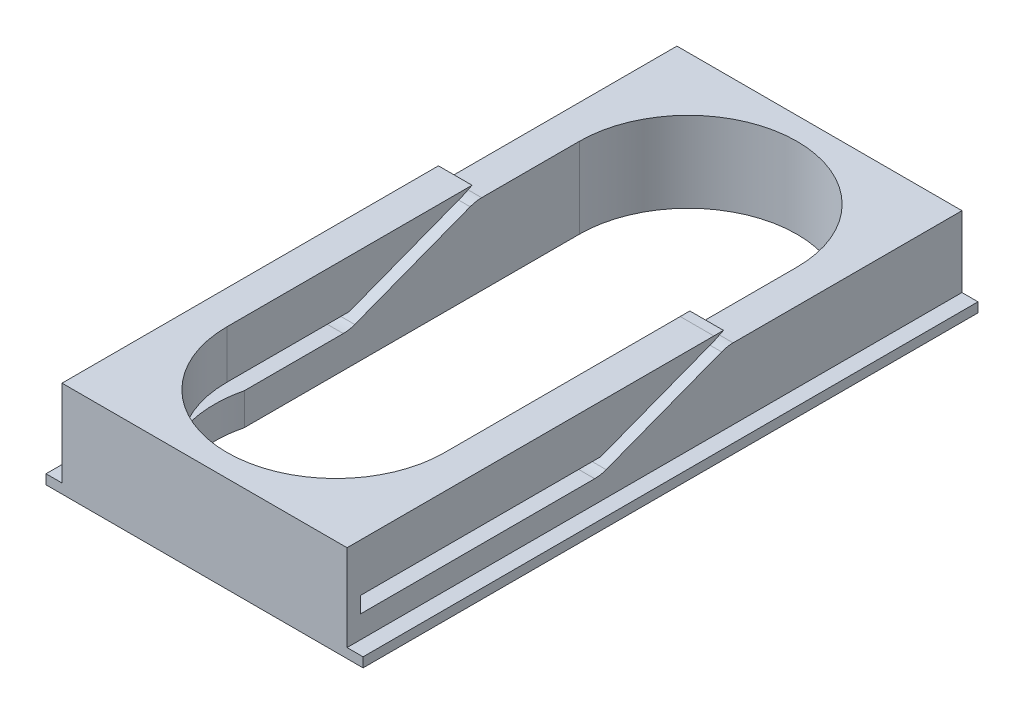
SolidWorks part; units mm, degrees
ref_plane "Front Plane" through (0, 0, 0) normal (0, 0, 1) x (1, 0, 0)
ref_plane "Top Plane" through (0, 0, 0) normal (0, 1, 0) x (1, 0, 0)
ref_plane "Right Plane" through (0, 0, 0) normal (1, 0, 0) x (0, 0, -1)
sketch "Sketch1" plane through (0, 0, 0) normal (0, 1, 0) x (1, 0, 0)
  line L0 (-10.5, -34.9563) -> (-10.5, 75.0437) construction
  line L1 (-55, -75.9563) -> (34, -75.9563)
  line L2 (-55, -75.9563) -> (-55, 116.0437)
  line L3 (-55, 116.0437) -> (34, 116.0437)
  line L4 (34, -75.9563) -> (34, 116.0437)
  line L5 (-44.5, -34.9563) -> (-44.5, 75.0437)
  line L6 (23.5, -34.9563) -> (23.5, 75.0437)
  arc A0 (-44.5, -34.9563) -> (23.5, -34.9563) centre (-10.5, -34.9563) ccw
  arc A1 (23.5, 75.0437) -> (-44.5, 75.0437) centre (-10.5, 75.0437) ccw
  point P6 (-10.5, 20.0437)
  dimension "D3" = 10.5
  dimension "D4" = 41
  dimension "D1" = 34
  dimension "D2" = 41
  dimension "D6" = 10.5
extrude "Boss-Extrude1" add sketch "Sketch1" along normal blind 30
sketch "Sketch2" plane through (0, 0, 0) normal (0, -1, 0) x (1, 0, 0)
  circle A0 centre (-10.5, 37.8388) radius 34.9994
extrude "Cut-Extrude1" cut sketch "Sketch2" against normal blind 10
sketch "Sketch3" plane through (34, 0, 0) normal (1, 0, 0) x (0, 0, -1)
  line L0 (-75.9563, 0) -> (116.0437, 0) construction
  line L1 (-71.7863, 10) -> (3.2137, 10)
  line L2 (-71.7863, 10) -> (-71.7863, 15)
  line L3 (-71.7863, 15) -> (3.2137, 15)
  line L4 (3.2137, 10) -> (3.2137, 15)
  dimension "D1" = 5
  dimension "D2" = 10
  dimension "D3" = 75
extrude "Cut-Extrude2" cut sketch "Sketch3" against normal blind 102
sketch "Sketch4" plane through (-55, 0, 0) normal (-1, 0, 0) x (0, 0, 1)
  line L1 (-40.9707, 29.4694) -> (-41.2116, 24.5617)
  line L4 (-40.9707, 29.4694) -> (-3.2137, 15)
  line L5 (-3.2137, 15) -> (-3.2137, 10)
  line L6 (-3.2137, 10) -> (-41.2116, 24.5617)
extrude "Cut-Extrude4" cut sketch "Sketch4" against normal blind 102
sketch "Sketch5" plane through (-55, 0, 0) normal (-1, 0, 0) x (0, 0, 1)
  line L2 (-42.5706, 30) -> (-40.9707, 30)
sketch "Sketch6" plane through (0, 30, 0) normal (0, 1, 0) x (1, 0, 0)
  line L0 (-44.5, 75.0437) -> (-44.5, -34.9563) construction
  line L1 (-55, 42.5706) -> (-44.5, 42.5706)
  line L2 (-55, 42.5706) -> (-55, 38.5706)
  line L3 (-55, 38.5706) -> (-44.5, 38.5706)
  line L4 (-44.5, 42.5706) -> (-44.5, 38.5706)
  line L7 (23.5, 42.5706) -> (23.5, 38.5706)
  line L8 (34, 38.5706) -> (23.5, 38.5706)
  line L9 (34, 42.5706) -> (34, 38.5706)
  line L10 (34, 42.5706) -> (23.5, 42.5706)
  dimension "D1" = 4
extrude "Cut-Extrude7" cut sketch "Sketch6" against normal blind 8
sketch "Sketch7" plane through (-55, 0, 0) normal (-1, 0, 0) x (0, 0, 1)
  line L0 (-38.5706, 23.5496) -> (-42.5706, 25.0825)
  line L1 (-42.5706, 22) -> (-42.5706, 30) construction
  line L2 (-42.5706, 25.0825) -> (-42.5706, 22)
  line L3 (-42.5706, 22) -> (-38.5706, 22)
  line L4 (-38.5706, 22) -> (-38.5706, 23.5496)
extrude "Boss-Extrude2" add sketch "Sketch7" against normal up to surface (10.5 mm away) up to face at (-44.5, 16.3944, -28.5016)
sketch "Sketch8" plane through (-55, 0, 0) normal (-1, 0, 0) x (0, 0, 1)
  line L0 (-42.5706, 25.0825) -> (-55.4025, 30)
  line L1 (-116.0437, 30) -> (-42.5706, 30) construction
  line L2 (-55.4025, 30) -> (-42.5706, 30)
  line L3 (-42.5706, 30) -> (-42.5706, 25.0825)
extrude "Cut-Extrude8" cut sketch "Sketch8" against normal blind 20.7678
sketch "Sketch9" plane through (34, 0, 0) normal (1, 0, 0) x (0, 0, -1)
  line L0 (38.5706, 23.5496) -> (42.5706, 25.0825)
  line L1 (42.5706, 22) -> (42.5706, 30) construction
  line L2 (42.5706, 25.0825) -> (42.5706, 22)
  line L3 (42.5706, 22) -> (38.5706, 22)
  line L4 (38.5706, 22) -> (38.5706, 23.5496)
extrude "Boss-Extrude3" add sketch "Sketch9" against normal up to surface (10.5 mm away) up to face at (23.5, 16.3944, -28.5016)
sketch "Sketch10" plane through (34, 0, 0) normal (1, 0, 0) x (0, 0, -1)
  line L0 (42.5706, 25.0825) -> (55.4025, 30)
  line L1 (42.5706, 30) -> (116.0437, 30) construction
  line L2 (55.4025, 30) -> (42.5706, 30)
  line L3 (42.5706, 30) -> (42.5706, 25.0825)
extrude "Cut-Extrude9" cut sketch "Sketch10" against normal blind 22.8125
sketch "Sketch11" plane through (34, 0, 0) normal (1, 0, 0) x (0, 0, -1)
  line L0 (38.5706, 28.5496) -> (41.5706, 30.0071)
  line L1 (41.5706, 30.0071) -> (38.5706, 30)
  line L4 (38.5706, 30) -> (38.5706, 28.5496)
  point P3 (55.4025, 30)
  dimension "D1" = 3
sketch "Sketch12" plane through (-55, 0, 0) normal (-1, 0, 0) x (0, 0, 1)
  line L0 (-38.5706, 30) -> (-41.5706, 30)
  line L1 (-41.5706, 30) -> (-38.5706, 28.5496)
  line L2 (-38.5706, 28.5496) -> (-38.5706, 30)
  point P3 (-55.4025, 30)
  dimension "D1" = 3
extrude "Boss-Extrude6" add sketch "Sketch12" against normal up to surface (10.5 mm away) up to face at (-44.5, 23.7099, -2.0885)
extrude "Boss-Extrude7" add sketch "Sketch11" against normal up to surface (10.5 mm away) up to face at (23.5, 13.3333, -24.9391)
fillet "Fillet1" radius 10 1 edges at (-49.75, 30, -55.4025)
fillet "Fillet2" radius 10 1 edges at (28.75, 30, -55.4025)
fillet "Fillet3" radius 10 1 edges at (-49.75, 10, -3.2137)
fillet "Fillet4" radius 10 1 edges at (28.75, 10, -3.2137)
sketch "Sketch14" plane through (34, 0, 0) normal (1, 0, 0) x (0, 0, -1)
  line L0 (42.7174, 25.1388) -> (116.0437, 25.1388)
  line L1 (53.6745, 29.3378) -> (4.9417, 10.6622) construction
  line L2 (116.0437, 30) -> (116.0437, 0) construction
  line L3 (42.7174, 25.1388) -> (53.6745, 29.3378)
  line L4 (53.6745, 29.3378) -> (57.253, 30)
  line L5 (57.253, 30) -> (116.0437, 30)
  line L6 (116.0437, 30) -> (116.0437, 25.1388)
extrude "Cut-Extrude11" cut sketch "Sketch14" against normal blind 99
sketch "Sketch15" plane through (34, 0, 0) normal (1, 0, 0) x (0, 0, -1)
  line L1 (51.0699, 31.494) -> (58.6241, 31.494)
  line L2 (51.0699, 31.494) -> (51.0699, 28.2348)
  line L3 (51.0699, 28.2348) -> (58.6241, 28.2348)
  line L4 (58.6241, 31.494) -> (58.6241, 28.2348)
extrude "Cut-Extrude12" cut sketch "Sketch15" against normal blind 99
fillet "Fillet5" radius 10 1 edges at (-49.75, 25.1388, -42.7174)
sketch "Sketch16" plane through (0, 0, 0) normal (0, -1, 0) x (-1, 0, 0)
  line L1 (-34, 116.0437) -> (-39, 116.0437)
  line L2 (-34, 116.0437) -> (-34, -75.9563)
  line L3 (-34, -75.9563) -> (-39, -75.9563)
  line L4 (-39, 116.0437) -> (-39, -75.9563)
  line L5 (55, 116.0437) -> (60, 116.0437)
  line L6 (55, 116.0437) -> (55, -75.9563)
  line L7 (55, -75.9563) -> (60, -75.9563)
  line L8 (60, 116.0437) -> (60, -75.9563)
  dimension "D1" = 5
extrude "Boss-Extrude8" add sketch "Sketch16" along normal blind 0.001 and the other way blind 3
